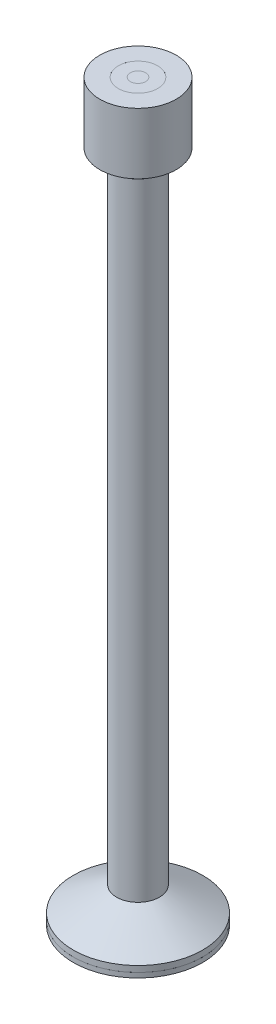
SolidWorks part; units mm, degrees
ref_plane "Alzado" through (0, 0, 0) normal (0, 0, 1) x (1, 0, 0)
ref_plane "Planta" through (0, 0, 0) normal (0, 1, 0) x (1, 0, 0)
ref_plane "Vista lateral" through (0, 0, 0) normal (1, 0, 0) x (0, 0, -1)
sketch "Croquis1" plane through (0, 0, 0) normal (0, 0, 1) x (1, 0, 0)
  line L0 (0, -22.5273) -> (0, 60.571) construction
  line L1 (5.375, 0) -> (5.375, 0.5)
  line L2 (5.375, 0.5) -> (1.78, 2.5)
  line L3 (1.78, 2.5) -> (1.78, 54.5)
  line L4 (1.78, 54.5) -> (3.1718, 55.5)
  line L5 (3.1718, 55.5) -> (3.1718, 60.571)
  line L6 (1.375, 54.9422) -> (1.375, 0)
  line L7 (1.375, 0) -> (5.375, 0)
  line L8 (0.375, 0.1) -> (0.375, 54.9422)
  line L9 (0.375, 54.9422) -> (0.635, 60.571)
  line L10 (0.375, 0.1) -> (0, 0.1)
  line L11 (0, 60.571) -> (0, 0.1)
  line L12 (0, 60.9797) -> (0, 62.2297) construction
  line L13 (3.1718, 60.571) -> (1.635, 60.571)
  line L14 (0.4604, 60.571) -> (-0.4604, 60.571) construction
  line L23 (1.375, 54.9422) -> (1.635, 60.571)
  line L26 (0.635, 60.571) -> (0.4424, 60.571)
  line L27 (0.4424, 60.571) -> (0, 60.571)
  dimension "D1" = 55
  dimension "D2" = 10.75
  dimension "D3" = 2
  dimension "D4" = 0.5
  dimension "D5" = 0.75
  dimension "D6" = 2.75
  dimension "D7" = 3.56
  dimension "D8" = 1
  dimension "D9" = 0.1
revolve "Revolución1" add sketch "Croquis1" angle 360 about L11
sketch "Croquis3" plane through (0, 0, 0) normal (0, 0, 1) x (1, 0, 0)
  line L0 (0, 55.5) -> (0, 0) construction
  line L1 (0.375, 54.9422) -> (0.635, 60.571)
  line L2 (0.635, 60.571) -> (-0.635, 60.571) construction
  line L3 (0.635, 60.571) -> (-0.635, 60.571) construction
  line L4 (0.635, 60.571) -> (1.635, 60.571)
  line L5 (1.375, 0.1) -> (0.375, 0.1)
  line L6 (0.635, 60.571) -> (0.4424, 60.571)
  line L7 (0.375, 0.1) -> (0.375, 54.9422)
  line L8 (0, 0.1) -> (0.375, 0.1)
  line L9 (0, 60.571) -> (0, 0.1)
  line L10 (0.375, 54.9422) -> (0.635, 60.571)
  line L12 (0.4424, 60.571) -> (0, 60.571)
  line L13 (0.375, 0.1) -> (0.375, 54.9422)
  line L20 (3.1718, 55.5) -> (3.1718, 60.571)
  line L21 (1.78, 54.5) -> (3.1718, 55.5)
  line L22 (1.78, 2.5) -> (1.78, 54.5)
  line L23 (5.375, 0.5) -> (1.78, 2.5)
  line L24 (5.375, 0) -> (5.375, 0.5)
  line L25 (1.375, 0) -> (5.375, 0)
  line L26 (1.375, 54.9422) -> (1.375, 0)
  line L27 (1.635, 60.571) -> (1.375, 54.9422)
  line L28 (1.635, 60.571) -> (1.375, 54.9422)
  line L29 (3.1718, 60.571) -> (1.635, 60.571)
  line L34 (1.375, 54.9422) -> (1.375, 0.1)
  dimension "D1" = 0
  dimension "D2" = 0
revolve "Revolución2" add sketch "Croquis3" angle 360 about L0
sketch "Croquis4" plane through (0, 0, 0) normal (0, -1, 0) x (1, 0, 0)
  circle A1 centre (0, 0) radius 1.375
  circle A2 centre (0, 0) radius 1.375
  dimension "D1" = 0
extrude "Saliente-Extruir1" add sketch "Croquis4" against normal up to surface (0.1 mm away) separate body up to face at (0, 0.1, 1.375)
sketch "Croquis5" plane through (0, 0, 0) normal (0, -1, 0) x (1, 0, 0)
  circle A0 centre (0, 0) radius 5.375 construction
  circle A1 centre (0, 0) radius 5.375
extrude "Saliente-Extruir2" add sketch "Croquis5" along normal blind 0.4
